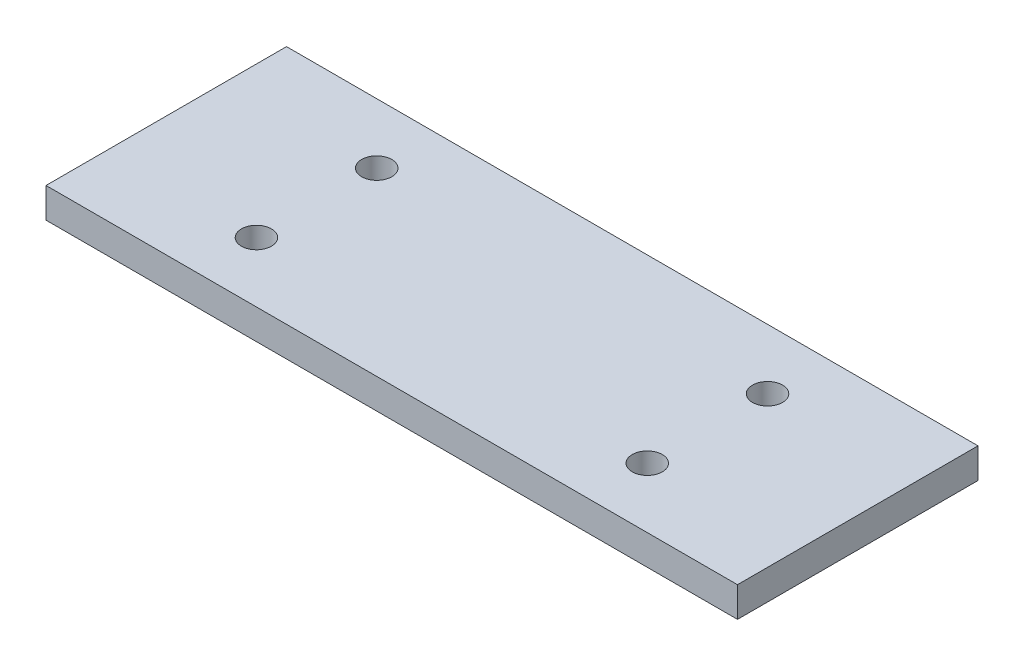
SolidWorks part; units mm, degrees
ref_plane "Front Plane" through (0, 0, 0) normal (0, 0, 1) x (1, 0, 0)
ref_plane "Top Plane" through (0, 0, 0) normal (0, 1, 0) x (1, 0, 0)
ref_plane "Right Plane" through (0, 0, 0) normal (1, 0, 0) x (0, 0, -1)
sketch "Sketch1" plane through (0, 0, 0) normal (0, 1, 0) x (1, 0, 0)
  line L1 (-57.5, 20) -> (57.5, 20)
  line L2 (-57.5, 20) -> (-57.5, -20)
  line L3 (-57.5, -20) -> (57.5, -20)
  line L4 (57.5, 20) -> (57.5, -20)
  circle A0 centre (-32.5, 10) radius 2.5
  circle A1 centre (32.5, 10) radius 2.5
  circle A2 centre (-32.5, -10) radius 2.5
  circle A3 centre (32.5, -10) radius 2.5
  point P0 (0, 0)
  point P6 (-32.5, 10)
  point P7 (32.5, 10)
  point P8 (32.5, -10)
  point P9 (-32.5, -10)
  dimension "D1" = 40
  dimension "D2" = 115
  dimension "D3" = 65
  dimension "D4" = 25
  dimension "D5" = 25
  dimension "D6" = 25
  dimension "D7" = 25
  dimension "D8" = 65
  dimension "D9" = 20
  dimension "D10" = 10
extrude "Boss-Extrude1" add sketch "Sketch1" along normal mid plane 5
